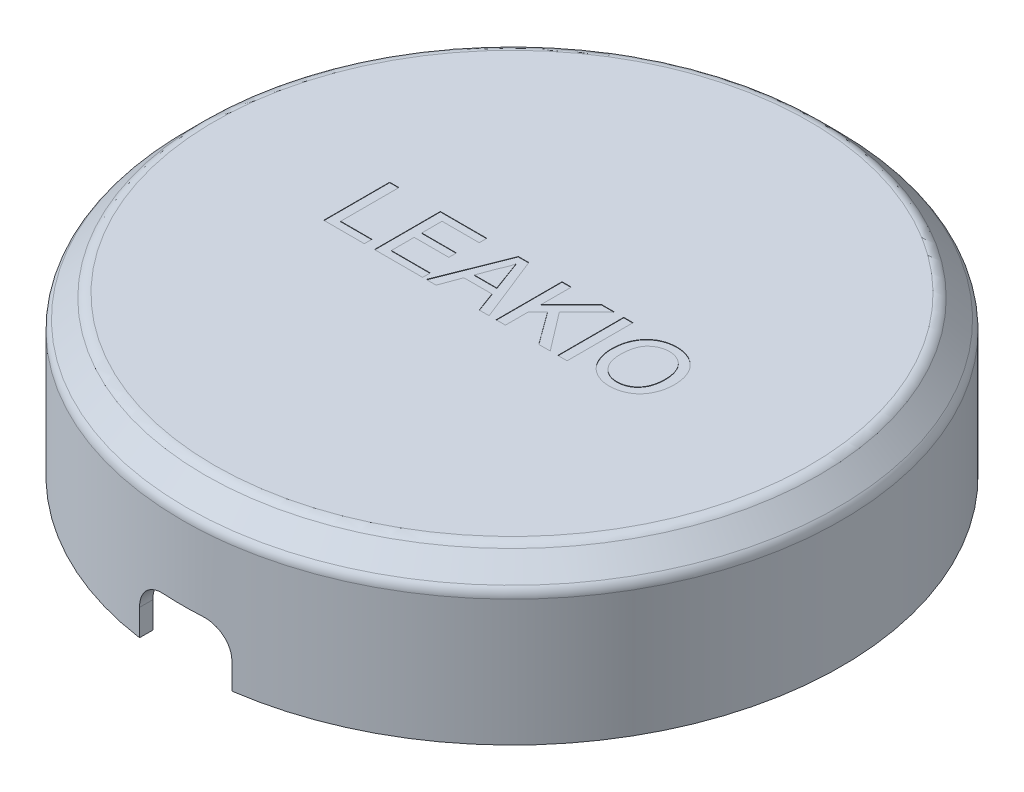
SolidWorks part; units mm, degrees
ref_plane "Front Plane" through (0, 0, 0) normal (0, 0, 1) x (1, 0, 0)
ref_plane "Top Plane" through (0, 0, 0) normal (0, 1, 0) x (1, 0, 0)
ref_plane "Right Plane" through (0, 0, 0) normal (1, 0, 0) x (0, 0, -1)
sketch "Sketch1" plane through (0, 0, 0) normal (0, 1, 0) x (1, 0, 0)
  circle A0 centre (0, 0) radius 25
  dimension "D1" = 50
extrude "Boss-Extrude1" add sketch "Sketch1" along normal blind 12
chamfer "Chamfer1" distance 2 angle 45 1 edges at (0, 12, 25)
shell "Shell2" thickness 1
sketch "Sketch4" plane through (0, 12, 0) normal (0, 1, 0) x (1, 0, 0)
  text T0 "LEAKIO" font "Century Gothic" height 5
extrude "Cut-Extrude1" cut sketch "Sketch4" against normal blind 0.05
sketch "Sketch5" plane through (0, 11.95, 0) normal (0, 1, 0) x (1, 0, 0)
  line L0 (5.8129, -2.3369) -> (6.518, -2.3369) construction
  line L1 (6.518, -2.3369) -> (6.518, 2.6631) construction
  line L2 (6.518, 2.6631) -> (5.8129, 2.6631) construction
  line L3 (5.8129, 2.6631) -> (5.8129, -2.3369) construction
  line L4 (1.1334, -2.3369) -> (1.8385, -2.3369) construction
  line L5 (1.8385, -2.3369) -> (1.8385, -0.6062) construction
  line L6 (1.8385, -0.6062) -> (2.5717, 0.126) construction
  line L7 (2.5717, 0.126) -> (4.3676, -2.3369) construction
  line L8 (4.3676, -2.3369) -> (5.2359, -2.3369) construction
  line L9 (5.2359, -2.3369) -> (3.0184, 0.5737) construction
  line L10 (3.0184, 0.5737) -> (5.1077, 2.6631) construction
  line L11 (5.1077, 2.6631) -> (4.1422, 2.6631) construction
  line L12 (4.1422, 2.6631) -> (1.8385, 0.3594) construction
  line L13 (1.8385, 0.3594) -> (1.8385, 2.6631) construction
  line L14 (1.8385, 2.6631) -> (1.1334, 2.6631) construction
  line L15 (1.1334, 2.6631) -> (1.1334, -2.3369) construction
  line L16 (-4.1661, -2.3369) -> (-3.4179, -2.3369) construction
  line L17 (-3.4179, -2.3369) -> (-2.849, -0.7985) construction
  line L18 (-2.849, -0.7985) -> (-0.7176, -0.7985) construction
  line L19 (-0.7176, -0.7985) -> (-0.1487, -2.3369) construction
  line L20 (-0.1487, -2.3369) -> (0.5995, -2.3369) construction
  line L21 (0.5995, -2.3369) -> (-1.3857, 2.6631) construction
  line L22 (-1.3857, 2.6631) -> (-2.1809, 2.6631) construction
  line L23 (-2.1809, 2.6631) -> (-4.1661, -2.3369) construction
  line L24 (-11.9435, -2.3369) -> (-8.8666, -2.3369) construction
  line L25 (-8.8666, -2.3369) -> (-8.8666, -1.76) construction
  line L26 (-8.8666, -1.76) -> (-11.2384, -1.76) construction
  line L27 (-11.2384, -1.76) -> (-11.2384, 2.6631) construction
  line L28 (-11.2384, 2.6631) -> (-11.9435, 2.6631) construction
  line L29 (-11.9435, 2.6631) -> (-11.9435, -2.3369) construction
  line L30 (-8.0974, -2.3369) -> (-4.4435, -2.3369) construction
  line L31 (-4.4435, -2.3369) -> (-4.4435, -1.76) construction
  line L32 (-4.4435, -1.76) -> (-7.3923, -1.76) construction
  line L33 (-7.3923, -1.76) -> (-7.3923, -0.0292) construction
  line L34 (-7.3923, -0.0292) -> (-4.7641, -0.0292) construction
  line L35 (-4.7641, -0.0292) -> (-4.7641, 0.5477) construction
  line L36 (-4.7641, 0.5477) -> (-7.3923, 0.5477) construction
  line L37 (-7.3923, 0.5477) -> (-7.3923, 2.0861) construction
  line L38 (-7.3923, 2.0861) -> (-4.5717, 2.0861) construction
  line L39 (-4.5717, 2.0861) -> (-4.5717, 2.6631) construction
  line L40 (-4.5717, 2.6631) -> (-8.0974, 2.6631) construction
  line L41 (-8.0974, 2.6631) -> (-8.0974, -2.3369) construction
  line L42 (5.8129, -2.3369) -> (6.518, -2.3369)
  line L43 (6.518, -2.3369) -> (6.518, 2.6631)
  line L44 (6.518, 2.6631) -> (5.8129, 2.6631)
  line L45 (5.8129, 2.6631) -> (5.8129, -2.3369)
  line L46 (1.1334, -2.3369) -> (1.8385, -2.3369)
  line L47 (1.8385, -2.3369) -> (1.8385, -0.6062)
  line L48 (1.8385, -0.6062) -> (2.5717, 0.126)
  line L49 (2.5717, 0.126) -> (4.3676, -2.3369)
  line L50 (4.3676, -2.3369) -> (5.2359, -2.3369)
  line L51 (5.2359, -2.3369) -> (3.0184, 0.5737)
  line L52 (3.0184, 0.5737) -> (5.1077, 2.6631)
  line L53 (5.1077, 2.6631) -> (4.1422, 2.6631)
  line L54 (4.1422, 2.6631) -> (1.8385, 0.3594)
  line L55 (1.8385, 0.3594) -> (1.8385, 2.6631)
  line L56 (1.8385, 2.6631) -> (1.1334, 2.6631)
  line L57 (1.1334, 2.6631) -> (1.1334, -2.3369)
  line L58 (-4.1661, -2.3369) -> (-3.4179, -2.3369)
  line L59 (-3.4179, -2.3369) -> (-2.849, -0.7985)
  line L60 (-2.849, -0.7985) -> (-0.7176, -0.7985)
  line L61 (-0.7176, -0.7985) -> (-0.1487, -2.3369)
  line L62 (-0.1487, -2.3369) -> (0.5995, -2.3369)
  line L63 (0.5995, -2.3369) -> (-1.3857, 2.6631)
  line L64 (-1.3857, 2.6631) -> (-2.1809, 2.6631)
  line L65 (-2.1809, 2.6631) -> (-4.1661, -2.3369)
  line L66 (-11.9435, -2.3369) -> (-8.8666, -2.3369)
  line L67 (-8.8666, -2.3369) -> (-8.8666, -1.76)
  line L68 (-8.8666, -1.76) -> (-11.2384, -1.76)
  line L69 (-11.2384, -1.76) -> (-11.2384, 2.6631)
  line L70 (-11.2384, 2.6631) -> (-11.9435, 2.6631)
  line L71 (-11.9435, 2.6631) -> (-11.9435, -2.3369)
  line L72 (-8.0974, -2.3369) -> (-4.4435, -2.3369)
  line L73 (-4.4435, -2.3369) -> (-4.4435, -1.76)
  line L74 (-4.4435, -1.76) -> (-7.3923, -1.76)
  line L75 (-7.3923, -1.76) -> (-7.3923, -0.0292)
  line L76 (-7.3923, -0.0292) -> (-4.7641, -0.0292)
  line L77 (-4.7641, -0.0292) -> (-4.7641, 0.5477)
  line L78 (-4.7641, 0.5477) -> (-7.3923, 0.5477)
  line L79 (-7.3923, 0.5477) -> (-7.3923, 2.0861)
  line L80 (-7.3923, 2.0861) -> (-4.5717, 2.0861)
  line L81 (-4.5717, 2.0861) -> (-4.5717, 2.6631)
  line L82 (-4.5717, 2.6631) -> (-8.0974, 2.6631)
  line L83 (-8.0974, 2.6631) -> (-8.0974, -2.3369)
  line L87 (-2.1248, 1.1627) -> (-2.6367, -0.2216)
  line L88 (-2.6367, -0.2216) -> (-0.9299, -0.2216)
  line L89 (-0.9299, -0.2216) -> (-1.4157, 1.0925)
  line L90 (-2.1248, 1.1627) -> (-2.6367, -0.2216)
  line L91 (-2.6367, -0.2216) -> (-0.9299, -0.2216)
  line L92 (-0.9299, -0.2216) -> (-1.4157, 1.0925)
  spline S0 degree 3 poles (-1990.8776, -80.9604) (28.3072, 11.3576) (6.9256, 5.0645) (7.4324, -0.2247) (7.4537, -0.3826) (7.4853, -0.5387) (7.5249, -0.6927) (7.5747, -0.8442) (7.6313, -0.9941) (7.6985, -1.1403) (7.7729, -1.2828) (7.8571, -1.4174) (7.9486, -1.5453) (8.0503, -1.6636) (8.1583, -1.7769) (8.276, -1.8808) (8.4014, -1.9773) (8.5346, -2.0653) (8.6743, -2.1444) (8.8199, -2.2123) (8.9697, -2.2707) (9.1243, -2.319) (9.2836, -2.3561) (9.4477, -2.3817) (14.9568, -2.9322) (21.5225, 18.8476) (-73.5921, -2000.5828) knots -4.005489 -4.005489 -4.005489 -4.005489 0.042093 0.083554 0.124992 0.166052 0.207381 0.248618 0.290057 0.332021 0.373735 0.415036 0.455409 0.495952 0.536368 0.57703 0.617971 0.659396 0.701152 0.742753 0.784285 0.826186 0.868591 0.911466 0.955303 5.171731 5.171731 5.171731 5.171731 only from (7.4154, 0.097) to (9.7872, -2.401) construction
  spline S1 degree 3 poles (79.5401, -2001.0874) (-1.9272, 16.9385) (4.5006, -2.8844) (10.1044, -2.3838) (10.2591, -2.3594) (10.4115, -2.3267) (10.5611, -2.2835) (10.7075, -2.2302) (10.8511, -2.1676) (10.9922, -2.0972) (11.1278, -2.0167) (11.2557, -1.9257) (11.3761, -1.8266) (11.4887, -1.7184) (11.592, -1.6002) (11.6885, -1.474) (11.7766, -1.3383) (11.8566, -1.1944) (11.9272, -1.0432) (11.9898, -0.8869) (12.0415, -0.7251) (12.085, -0.5587) (12.1175, -0.3872) (12.142, -0.2111) (12.6417, 6.2939) (-7.2229, 13.4753) (2011.3267, -53.0079) knots -4.181962 -4.181962 -4.181962 -4.181962 0.040917 0.081206 0.121044 0.160801 0.20044 0.240141 0.27998 0.320332 0.360792 0.400579 0.440342 0.480112 0.519955 0.560443 0.601634 0.64374 0.686389 0.729297 0.772543 0.816374 0.860888 0.906038 0.95244 5.851848 5.851848 5.851848 5.851848 only from (9.7872, -2.401) to (12.159, 0.155) construction
  spline S2 degree 3 poles (2011.6534, 42.3167) (-6.1458, -13.5317) (12.6181, -6.2393) (12.1431, 0.5155) (12.1192, 0.6892) (12.0892, 0.8584) (12.0474, 1.0224) (11.9975, 1.1812) (11.9394, 1.3357) (11.8714, 1.4841) (11.7953, 1.6269) (11.7106, 1.762) (11.6167, 1.8882) (11.5166, 2.0079) (11.406, 2.1173) (11.2886, 2.2201) (11.1628, 2.3147) (11.029, 2.4003) (10.8892, 2.4768) (10.7453, 2.5452) (10.5961, 2.6004) (10.4431, 2.6471) (10.286, 2.6827) (10.1245, 2.7093) (4.3785, 3.2257) (-2.1734, -17.2366) (74.9237, 2001.6053) knots -5.029529 -5.029529 -5.029529 -5.029529 0.046666 0.092161 0.136649 0.180448 0.223293 0.265781 0.307491 0.349241 0.390297 0.430963 0.470884 0.510312 0.549967 0.589534 0.629402 0.66999 0.710719 0.750975 0.79155 0.832033 0.873092 0.914413 0.956901 5.273034 5.273034 5.273034 5.273034 only from (12.159, 0.155) to (9.7902, 2.7272) construction
  spline S3 degree 3 poles (-111.2079, 1998.9844) (24.1505, -24.2354) (15.7546, 3.5944) (9.2921, 2.6869) (9.0587, 2.6336) (8.8372, 2.5574) (8.6283, 2.4581) (8.431, 2.3379) (8.2471, 2.1938) (8.0745, 2.0316) (7.9199, 1.848) (7.7833, 1.648) (7.6701, 1.4296) (7.577, 1.1953) (7.5036, 0.9445) (7.4522, 0.6769) (6.5923, -7.0534) (33.92, -16.1975) (-1990.7427, 84.2629) knots -4.703221 -4.703221 -4.703221 -4.703221 0.064217 0.125675 0.185372 0.243705 0.301102 0.358698 0.416748 0.476136 0.536238 0.596504 0.657597 0.72047 0.7855 0.853425 0.924774 6.615557 6.615557 6.615557 6.615557 only from (9.7902, 2.7272) to (7.4154, 0.097) construction
  spline S4 degree 3 poles (7.4154, 0.097) (7.416, 0.0428) (7.4171, -0.0646) (7.4324, -0.2247) (7.4537, -0.3826) (7.4853, -0.5387) (7.5249, -0.6927) (7.5747, -0.8442) (7.6313, -0.9941) (7.6985, -1.1403) (7.7729, -1.2828) (7.8571, -1.4174) (7.9486, -1.5453) (8.0503, -1.6636) (8.1583, -1.7769) (8.276, -1.8808) (8.4014, -1.9773) (8.5346, -2.0653) (8.6743, -2.1444) (8.8199, -2.2123) (8.9697, -2.2707) (9.1243, -2.319) (9.2836, -2.3561) (9.4477, -2.3817) (9.6159, -2.3985) (9.7298, -2.4002) (9.7872, -2.401) knots 0 0 0 0 0.042093 0.083554 0.124992 0.166052 0.207381 0.248618 0.290057 0.332021 0.373735 0.415036 0.455409 0.495952 0.536368 0.57703 0.617971 0.659396 0.701152 0.742753 0.784285 0.826186 0.868591 0.911466 0.955303 1 1 1 1
  spline S5 degree 3 poles (9.7872, -2.401) (9.8407, -2.4) (9.9467, -2.3979) (10.1044, -2.3838) (10.2591, -2.3594) (10.4115, -2.3267) (10.5611, -2.2835) (10.7075, -2.2302) (10.8511, -2.1676) (10.9922, -2.0972) (11.1278, -2.0167) (11.2557, -1.9257) (11.3761, -1.8266) (11.4887, -1.7184) (11.592, -1.6002) (11.6885, -1.474) (11.7766, -1.3383) (11.8566, -1.1944) (11.9272, -1.0432) (11.9898, -0.8869) (12.0415, -0.7251) (12.085, -0.5587) (12.1175, -0.3872) (12.142, -0.2111) (12.1559, -0.0298) (12.158, 0.0929) (12.159, 0.155) knots 0 0 0 0 0.040917 0.081206 0.121044 0.160801 0.20044 0.240141 0.27998 0.320332 0.360792 0.400579 0.440342 0.480112 0.519955 0.560443 0.601634 0.64374 0.686389 0.729297 0.772543 0.816374 0.860888 0.906038 0.95244 1 1 1 1
  spline S6 degree 3 poles (12.159, 0.155) (12.1579, 0.2162) (12.1556, 0.3369) (12.1431, 0.5155) (12.1192, 0.6892) (12.0892, 0.8584) (12.0474, 1.0224) (11.9975, 1.1812) (11.9394, 1.3357) (11.8714, 1.4841) (11.7953, 1.6269) (11.7106, 1.762) (11.6167, 1.8882) (11.5166, 2.0079) (11.406, 2.1173) (11.2886, 2.2201) (11.1628, 2.3147) (11.029, 2.4003) (10.8892, 2.4768) (10.7453, 2.5452) (10.5961, 2.6004) (10.4431, 2.6471) (10.286, 2.6827) (10.1245, 2.7093) (9.9588, 2.7242) (9.8467, 2.7262) (9.7902, 2.7272) knots 0 0 0 0 0.046666 0.092161 0.136649 0.180448 0.223293 0.265781 0.307491 0.349241 0.390297 0.430963 0.470884 0.510312 0.549967 0.589534 0.629402 0.66999 0.710719 0.750975 0.79155 0.832033 0.873092 0.914413 0.956901 1 1 1 1
  spline S7 degree 3 poles (9.7902, 2.7272) (9.7046, 2.7252) (9.5371, 2.7213) (9.2921, 2.6869) (9.0587, 2.6336) (8.8372, 2.5574) (8.6283, 2.4581) (8.431, 2.3379) (8.2471, 2.1938) (8.0745, 2.0316) (7.9199, 1.848) (7.7833, 1.648) (7.6701, 1.4296) (7.577, 1.1953) (7.5036, 0.9445) (7.4522, 0.6769) (7.4206, 0.3925) (7.4172, 0.1972) (7.4154, 0.097) knots 0 0 0 0 0.064217 0.125675 0.185372 0.243705 0.301102 0.358698 0.416748 0.476136 0.536238 0.596504 0.657597 0.72047 0.7855 0.853425 0.924774 1 1 1 1
  spline S10 degree 3 poles (2887.5316, -804.8663) (-29.6975, 25.5683) (0.6009, 8.9195) (-1.921, 1.616) (-4.9185, -5.9032) (-38.2173, 0.4292) (2719.4714, -1260.7247) knots -22.708305 -22.708305 -22.708305 -22.708305 0.247294 0.495608 0.746359 24.824677 24.824677 24.824677 24.824677 only from (-1.7833, 2.0861) to (-2.1248, 1.1627)
  spline S11 degree 3 poles (2824.5708, 1007.4934) (-4.781, -27.0341) (2.9793, -10.5779) (-1.525, 1.3868) (-1.5746, 1.5238) (-1.6233, 1.6516) (-1.6672, 1.7719) (-1.7077, 1.8841) (-4.1671, 8.2264) (8.0295, 19.9743) (-2820.4599, -1024.2915) knots -35.765737 -35.765737 -35.765737 -35.765737 0.153148 0.299433 0.436426 0.565671 0.686508 0.799269 0.903395 19.947809 19.947809 19.947809 19.947809 only from (-1.4157, 1.0925) to (-1.7833, 2.0861)
  spline S12 degree 3 poles (-1.7833, 2.0861) (-1.8024, 2.007) (-1.8407, 1.8484) (-1.921, 1.616) (-2.0128, 1.3857) (-2.0873, 1.2373) (-2.1248, 1.1627) knots 0 0 0 0 0.247294 0.495608 0.746359 1 1 1 1
  spline S13 degree 3 poles (-1.4157, 1.0925) (-1.4343, 1.1433) (-1.4707, 1.2426) (-1.525, 1.3868) (-1.5746, 1.5238) (-1.6233, 1.6516) (-1.6672, 1.7719) (-1.7077, 1.8841) (-1.7477, 1.9873) (-1.7717, 2.054) (-1.7833, 2.0861) knots 0 0 0 0 0.153148 0.299433 0.436426 0.565671 0.686508 0.799269 0.903395 1 1 1 1
  dimension "D1" = 0
extrude "Boss-Extrude2" add sketch "Sketch5" along normal blind 0.02
sketch "Sketch6" plane through (0, 0, 0) normal (0, 0, 1) x (1, 0, 0)
  line L0 (-25, 0) -> (25, 0) construction
  line L1 (-3.5, 0) -> (3.5, 0)
  line L2 (-3.5, 0) -> (-3.5, 4)
  line L3 (-3.5, 4) -> (3.5, 4)
  line L4 (3.5, 0) -> (3.5, 4)
  line L5 (0, 4) -> (0, 0) construction
  dimension "D1" = 7
  dimension "D2" = 4
extrude "Cut-Extrude2" cut sketch "Sketch6" along normal through all
fillet "Fillet1" radius 2 2 edges at (3.5, 4, 24.2486) (-3.5, 4, 24.2486)
sketch "Sketch7" plane through (0, 11, 0) normal (0, -1, 0) x (1, 0, 0)
  line L1 (-15, 15) -> (15, 15) construction
  line L2 (-15, 15) -> (-15, -15) construction
  line L3 (-15, -15) -> (15, -15) construction
  line L4 (15, 15) -> (15, -15) construction
  line L5 (-15, 15) -> (15, -15) construction
  line L6 (-15, -15) -> (15, 15) construction
  circle A0 centre (-15, 15) radius 1.5
  circle A1 centre (15, 15) radius 1.5
  circle A2 centre (-15, -15) radius 1.5
  circle A3 centre (15, -15) radius 1.5
  point P0 (0, 0)
  dimension "D2" = 3
  dimension "D3" = 3
  dimension "D4" = 3
  dimension "D5" = 3
  dimension "D1" = 30
extrude "Boss-Extrude3" add sketch "Sketch7" along normal up to surface (11 mm away) up to face at (0, 0, -0.1257)
sketch "Sketch8" plane through (0, 11, 0) normal (0, -1, 0) x (1, 0, 0)
  line L0 (-16, 0) -> (16, 0) construction
  line L1 (-16, 10) -> (-14, 10)
  line L2 (-16, 10) -> (-16, -10)
  line L3 (-16, -10) -> (-14, -10)
  line L4 (-14, 10) -> (-14, -10)
  line L5 (14, 10) -> (16, 10)
  line L6 (14, 10) -> (14, -10)
  line L7 (14, -10) -> (16, -10)
  line L8 (16, 10) -> (16, -10)
  dimension "D1" = 2
  dimension "D2" = 32
  dimension "D3" = 20
extrude "Boss-Extrude4" add sketch "Sketch8" along normal blind 2
sketch "Sketch9" plane through (0, 0, 0) normal (0, -1, 0) x (1, 0, 0)
  circle A0 centre (-15, 15) radius 1
  circle A1 centre (15, 15) radius 1
  circle A2 centre (15, -15) radius 1
  circle A3 centre (-15, -15) radius 1
  dimension "D1" = 2
  dimension "D2" = 2
  dimension "D3" = 2
  dimension "D4" = 2
extrude "Cut-Extrude3" cut sketch "Sketch9" against normal blind 4
fillet "Fillet2" radius 1 2 edges at (0, 10, 25) (0, 12, 23)
